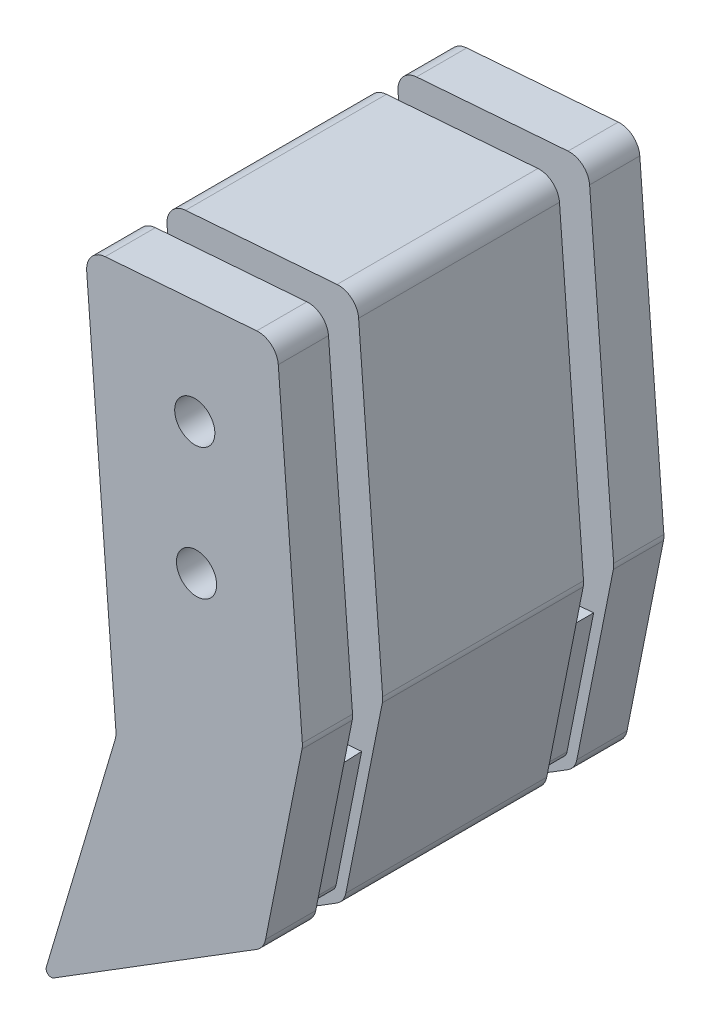
SolidWorks part; units mm, degrees
ref_plane "前视基准面" through (0, 0, 0) normal (0, 0, 1) x (1, 0, 0)
ref_plane "上视基准面" through (0, 0, 0) normal (0, 1, 0) x (1, 0, 0)
ref_plane "右视基准面" through (0, 0, 0) normal (1, 0, 0) x (0, 0, -1)
sketch "草图1" plane through (0, 0, 0) normal (0, 0, 1) x (1, 0, 0)
  line L0 (299.0977, 57.4833) -> (301.7357, 22.832)
  line L1 (315.185, 58.708) -> (317.2959, 30.9803)
  line L2 (317.2959, 30.9803) -> (313.4423, 11.6359)
  line L3 (299.0977, 57.4833) -> (315.185, 58.708)
  line L4 (313.4423, 11.6359) -> (294.7308, 0)
  line L5 (294.7308, 0) -> (301.7357, 22.832)
extrude "凸台-拉伸1" add sketch "草图1" along normal blind 36
ref_plane "基准面1" through (0, 0, 18) normal (0, 0, 1) x (1, 0, 0)
sketch "草图2" plane through (-2.6275, 34.5134, 0) normal (-0.0759, 0.9971, 0) x (0.9971, 0.0759, 0)
  line L4 (318.7321, 0) -> (302.5983, 0)
  line L5 (302.5983, 0) -> (302.5983, -36)
  line L6 (302.5983, -36) -> (318.7321, -36)
  line L7 (318.7321, -36) -> (318.7321, 0)
  line L8 (318.7321, 0) -> (302.5983, 0)
  line L9 (302.5983, 0) -> (302.5983, -36)
  line L10 (302.5983, -36) -> (318.7321, -36)
  line L11 (318.7321, -36) -> (318.7321, 0)
  dimension "D1" = 0
extrude "凸台-拉伸2" add sketch "草图2" along normal blind 6
sketch "草图3" plane through (0, 0, 36) normal (0, 0, 1) x (1, 0, 0)
  line L0 (298.6423, 63.466) -> (301.7357, 22.832) construction
  line L1 (298.6423, 63.466) -> (301.7357, 22.832)
  line L2 (301.7357, 22.832) -> (294.7308, 0) construction
  line L3 (301.7357, 22.832) -> (294.7308, 0)
  line L6 (298.6423, 63.466) -> (295.651, 63.2382)
  line L7 (295.651, 63.2382) -> (298.7444, 22.6043)
  line L9 (294.7308, 0) -> (291.4057, -2.0677)
  line L10 (291.4057, -2.0677) -> (298.7444, 22.6043)
extrude "凸台-拉伸3" add sketch "草图3" against normal up to surface (36 mm away) up to face at (306.7627, 32.2675, 0)
fillet "圆角2" radius 0.5 1 edges at (291.4057, -2.0677, 18)
fillet "圆角4" radius 2 5 edges at (313.4423, 11.6359, 18) (298.7444, 22.6043, 18) (317.2959, 30.9803, 18) (295.651, 63.2382, 18) (314.7295, 64.6907, 18)
ref_plane "基准面2" through (0, 0, 31) normal (0, 0, 1) x (1, 0, 0)
sketch "草图4" plane through (0, 0, 31) normal (0, 0, 1) x (1, 0, 0)
  line L0 (312.8112, 63.5417) -> (297.7211, 62.3929)
  line L1 (296.7999, 61.3199) -> (299.7134, 23.0484)
  line L2 (299.5976, 21.9653) -> (293.1155, 0.1731)
  line L3 (293.1155, 0.1731) -> (312.1782, 12.0274)
  line L4 (312.6309, 12.6813) -> (316.2615, 30.9066)
  line L5 (316.2779, 31.1779) -> (313.8842, 62.6205)
  line L6 (292.5246, -1.3719) -> (312.7063, 11.1782)
  line L7 (313.6116, 12.4859) -> (317.2423, 30.7112)
  line L8 (317.275, 31.2538) -> (314.8814, 62.6964)
  line L9 (312.7353, 64.5389) -> (297.6452, 63.3901)
  line L10 (295.8028, 61.244) -> (298.7163, 22.9725)
  line L11 (298.6391, 22.2504) -> (291.7813, -0.8048)
  line L12 (292.5246, -1.3719) -> (312.7063, 11.1782)
  line L13 (313.6116, 12.4859) -> (317.2423, 30.7112)
  line L14 (317.275, 31.2538) -> (314.8814, 62.6964)
  line L15 (312.7353, 64.5389) -> (297.6452, 63.3901)
  line L16 (295.8028, 61.244) -> (298.7163, 22.9725)
  line L17 (298.6391, 22.2504) -> (291.7813, -0.8048)
  arc A0 (297.7211, 62.3929) -> (296.7999, 61.3199) centre (297.797, 61.3958) ccw
  arc A1 (299.5976, 21.9653) -> (299.7134, 23.0484) centre (296.7221, 22.8206) ccw
  arc A2 (293.1155, 0.1731) -> (293.1155, 0.1731) centre (293.1155, 0.1731) ccw
  arc A3 (312.1782, 12.0274) -> (312.6309, 12.6813) centre (311.6502, 12.8766) ccw
  arc A4 (316.2615, 30.9066) -> (316.2779, 31.1779) centre (315.2808, 31.102) ccw
  arc A5 (313.8842, 62.6205) -> (312.8112, 63.5417) centre (312.8871, 62.5446) ccw
  arc A6 (312.7063, 11.1782) -> (313.6116, 12.4859) centre (311.6502, 12.8766) ccw
  arc A7 (317.2423, 30.7112) -> (317.275, 31.2538) centre (315.2808, 31.102) ccw
  arc A8 (314.8814, 62.6964) -> (312.7353, 64.5389) centre (312.8871, 62.5446) ccw
  arc A9 (297.6452, 63.3901) -> (295.8028, 61.244) centre (297.797, 61.3958) ccw
  arc A10 (298.6391, 22.2504) -> (298.7163, 22.9725) centre (296.7221, 22.8206) ccw
  arc A11 (291.7813, -0.8048) -> (292.5246, -1.3719) centre (292.2606, -0.9473) ccw
  arc A12 (312.7063, 11.1782) -> (313.6116, 12.4859) centre (311.6502, 12.8766) ccw
  arc A13 (317.2423, 30.7112) -> (317.275, 31.2538) centre (315.2808, 31.102) ccw
  arc A14 (314.8814, 62.6964) -> (312.7353, 64.5389) centre (312.8871, 62.5446) ccw
  arc A15 (297.6452, 63.3901) -> (295.8028, 61.244) centre (297.797, 61.3958) ccw
  arc A16 (298.6391, 22.2504) -> (298.7163, 22.9725) centre (296.7221, 22.8206) ccw
  arc A17 (291.7813, -0.8048) -> (292.5246, -1.3719) centre (292.2606, -0.9473) ccw
  dimension "D1" = 0
  dimension "D2" = 1
extrude "切除-拉伸1" cut sketch "草图4" against normal blind 4
mirror "镜向1" about plane through (0, 0, 18) normal (0, 0, 1) of "切除-拉伸1"
sketch "草图5" plane through (316.8153, 24.1187, 0) normal (0.9971, 0.0759, 0) x (0, 0, -1)
  line L0 (-9, 29.0059) -> (-5, 29.0059)
  line L3 (-9, 7.0796) -> (-9, 1.9841)
  line L4 (-5, 7.0796) -> (-5, 38.6132)
  line L5 (-5, 38.6132) -> (-9, 38.6132)
  line L6 (-9, 38.6132) -> (-9, 7.0796)
  line L7 (-9, 7.0796) -> (-5, 7.0796)
  line L8 (-5, 7.0796) -> (-5, 29.0059)
  line L10 (-9, 29.0059) -> (-9, 7.0796)
  line L12 (-31, 38.6132) -> (-31, 7.0796)
  line L13 (-31, 7.0796) -> (-27, 7.0796)
  line L14 (-27, 7.0796) -> (-27, 38.6132)
  line L15 (-27, 38.6132) -> (-31, 38.6132)
  line L16 (-31, 29.0059) -> (-31, 7.0796)
  line L18 (-27, 7.0796) -> (-27, 29.0059)
  line L20 (-9, 1.9841) -> (-5, 1.9841)
  line L21 (-5, 1.9841) -> (-5, 7.0796)
  line L23 (-31, 7.0796) -> (-31, 1.3277)
  line L24 (-27, 7.0796) -> (-27, 1.5448)
  line L25 (-27, 29.0059) -> (-31, 29.0059)
  arc A0 (-27, 1.5448) -> (-31, 1.3277) centre (-9, -367.0247) ccw
  dimension "D1" = 0
  dimension "D2" = 0
extrude "切除-拉伸2" cut sketch "草图5" against normal through all
extrude "切除-拉伸3" cut sketch "草图6" against normal through all and the other way through all
sketch "草图6" plane through (0.5048, 7.5794, 36) normal (0, 0, 1) x (1, -0.0067, 0)
  circle A1 centre (305.1617, 31.8714) radius 2
  circle A3 centre (309.4331, 38.2783) radius 2
sketch "草图7" [suppressed] plane through (0, 0, 27) normal (0, 0, 1) x (1, 0, 0)
  line L6 (295.8028, 61.244) -> (298.7163, 22.9725)
  line L7 (298.6391, 22.2504) -> (291.7813, -0.8048)
  line L8 (292.5246, -1.3719) -> (312.7063, 11.1782)
  line L9 (313.6116, 12.4859) -> (317.2423, 30.7112)
  line L10 (317.275, 31.2538) -> (314.8814, 62.6964)
  line L11 (312.7353, 64.5389) -> (297.6452, 63.3901)
  line L12 (295.8028, 61.244) -> (298.7163, 22.9725)
  line L13 (298.6391, 22.2504) -> (291.7813, -0.8048)
  line L14 (292.5246, -1.3719) -> (312.7063, 11.1782)
  line L15 (313.6116, 12.4859) -> (317.2423, 30.7112)
  line L16 (317.275, 31.2538) -> (314.8814, 62.6964)
  line L17 (312.7353, 64.5389) -> (297.6452, 63.3901)
  circle A0 centre (310.1864, 43.7924) radius 2 construction
  circle A1 centre (310.1864, 43.7924) radius 2
  circle A2 centre (305.8724, 37.4141) radius 2 construction
  circle A3 centre (305.8724, 37.4141) radius 2
  arc A6 (298.6391, 22.2504) -> (298.7163, 22.9725) centre (296.7221, 22.8206) ccw
  arc A7 (291.7813, -0.8048) -> (292.5246, -1.3719) centre (292.2606, -0.9473) ccw
  arc A8 (312.7063, 11.1782) -> (313.6116, 12.4859) centre (311.6502, 12.8766) ccw
  arc A9 (317.2423, 30.7112) -> (317.275, 31.2538) centre (315.2808, 31.102) ccw
  arc A10 (314.8814, 62.6964) -> (312.7353, 64.5389) centre (312.8871, 62.5446) ccw
  arc A11 (297.6452, 63.3901) -> (295.8028, 61.244) centre (297.797, 61.3958) ccw
  arc A12 (298.6391, 22.2504) -> (298.7163, 22.9725) centre (296.7221, 22.8206) ccw
  arc A13 (291.7813, -0.8048) -> (292.5246, -1.3719) centre (292.2606, -0.9473) ccw
  arc A14 (312.7063, 11.1782) -> (313.6116, 12.4859) centre (311.6502, 12.8766) ccw
  arc A15 (317.2423, 30.7112) -> (317.275, 31.2538) centre (315.2808, 31.102) ccw
  arc A16 (314.8814, 62.6964) -> (312.7353, 64.5389) centre (312.8871, 62.5446) ccw
  arc A17 (297.6452, 63.3901) -> (295.8028, 61.244) centre (297.797, 61.3958) ccw
  dimension "D1" = 0
extrude "凸台-拉伸4" [suppressed] add sketch "草图7" along normal blind 1
sketch "草图8" [suppressed] plane through (0, 0, 9) normal (0, 0, -1) x (-1, 0, 0)
  line L6 (-298.7163, 22.9725) -> (-295.8028, 61.244)
  line L7 (-297.6452, 63.3901) -> (-312.7353, 64.5389)
  line L8 (-314.8814, 62.6964) -> (-317.275, 31.2538)
  line L9 (-317.2423, 30.7112) -> (-313.6116, 12.4859)
  line L10 (-312.7063, 11.1782) -> (-292.5246, -1.3719)
  line L11 (-291.7813, -0.8048) -> (-298.6391, 22.2504)
  line L12 (-298.7163, 22.9725) -> (-295.8028, 61.244)
  line L13 (-297.6452, 63.3901) -> (-312.7353, 64.5389)
  line L14 (-314.8814, 62.6964) -> (-317.275, 31.2538)
  line L15 (-317.2423, 30.7112) -> (-313.6116, 12.4859)
  line L16 (-312.7063, 11.1782) -> (-292.5246, -1.3719)
  line L17 (-291.7813, -0.8048) -> (-298.6391, 22.2504)
  circle A0 centre (-305.8724, 37.4141) radius 2 construction
  circle A1 centre (-305.8724, 37.4141) radius 2
  circle A2 centre (-310.1864, 43.7924) radius 2 construction
  circle A3 centre (-310.1864, 43.7924) radius 2
  arc A6 (-298.7163, 22.9725) -> (-298.6391, 22.2504) centre (-296.7221, 22.8206) ccw
  arc A7 (-295.8028, 61.244) -> (-297.6452, 63.3901) centre (-297.797, 61.3958) ccw
  arc A8 (-312.7353, 64.5389) -> (-314.8814, 62.6964) centre (-312.8871, 62.5446) ccw
  arc A9 (-317.275, 31.2538) -> (-317.2423, 30.7112) centre (-315.2808, 31.102) ccw
  arc A10 (-313.6116, 12.4859) -> (-312.7063, 11.1782) centre (-311.6502, 12.8766) ccw
  arc A11 (-292.5246, -1.3719) -> (-291.7813, -0.8048) centre (-292.2606, -0.9473) ccw
  arc A12 (-298.7163, 22.9725) -> (-298.6391, 22.2504) centre (-296.7221, 22.8206) ccw
  arc A13 (-295.8028, 61.244) -> (-297.6452, 63.3901) centre (-297.797, 61.3958) ccw
  arc A14 (-312.7353, 64.5389) -> (-314.8814, 62.6964) centre (-312.8871, 62.5446) ccw
  arc A15 (-317.275, 31.2538) -> (-317.2423, 30.7112) centre (-315.2808, 31.102) ccw
  arc A16 (-313.6116, 12.4859) -> (-312.7063, 11.1782) centre (-311.6502, 12.8766) ccw
  arc A17 (-292.5246, -1.3719) -> (-291.7813, -0.8048) centre (-292.2606, -0.9473) ccw
  dimension "D1" = 0
extrude "凸台-拉伸5" [suppressed] add sketch "草图8" along normal blind 1
sketch "草图9" plane through (316.8153, 24.1187, 0) normal (0.9971, 0.0759, 0) x (0, 0, -1)
  line L0 (-9, 38.6132) -> (-9, 41.4603)
  line L1 (-9, 41.4603) -> (-5, 41.4603)
  line L2 (-5, 41.4603) -> (-5, 38.6132)
  line L3 (-31, 38.6132) -> (-31, 44.4228)
  line L4 (-9, 38.6132) -> (-9, 29.0059)
  line L5 (-9, 29.0059) -> (-5, 29.0059)
  line L6 (-5, 29.0059) -> (-5, 38.6132)
  line L7 (-5, 38.6132) -> (-9, 38.6132)
  line L8 (-9, 38.6132) -> (-9, 29.0059)
  line L9 (-9, 29.0059) -> (-5, 29.0059)
  line L10 (-5, 29.0059) -> (-5, 38.6132)
  line L12 (-31, 44.4228) -> (-27, 44.4228)
  line L13 (-27, 44.4228) -> (-27, 38.6132)
  line L15 (-31, 29.0059) -> (-27, 29.0059)
  line L16 (-27, 29.0059) -> (-27, 38.6132)
  line L17 (-27, 38.6132) -> (-31, 38.6132)
  line L18 (-31, 38.6132) -> (-31, 29.0059)
  line L19 (-31, 29.0059) -> (-27, 29.0059)
  line L20 (-27, 29.0059) -> (-27, 38.6132)
  line L22 (-31, 38.6132) -> (-31, 29.0059)
  dimension "D2" = 0
  dimension "D1" = 0
extrude "切除-拉伸4" cut sketch "草图9" against normal through all
extrude "切除-拉伸5" cut sketch "草图10" against normal through all
sketch "草图10" plane through (66.8668, -81.0923, 36) normal (0, 0, 1) x (0.7884, 0.6152, 0)
  circle A1 centre (264.0005, -51.5968) radius 2
  circle A3 centre (271.8529, -41.2447) radius 2
  point P1 (264.0005, -51.5968)
sketch "草图11" plane through (0, 0, 27) normal (0, 0, 1) x (1, 0, 0)
  line L6 (312.7353, 64.5389) -> (297.6452, 63.3901)
  line L7 (295.8028, 61.244) -> (298.7163, 22.9725)
  line L8 (298.6391, 22.2504) -> (291.7813, -0.8048)
  line L9 (292.5246, -1.3719) -> (312.7063, 11.1782)
  line L10 (313.6116, 12.4859) -> (317.2423, 30.7112)
  line L11 (317.275, 31.2538) -> (314.8814, 62.6964)
  line L12 (312.7353, 64.5389) -> (297.6452, 63.3901)
  line L13 (295.8028, 61.244) -> (298.7163, 22.9725)
  line L14 (298.6391, 22.2504) -> (291.7813, -0.8048)
  line L15 (292.5246, -1.3719) -> (312.7063, 11.1782)
  line L16 (313.6116, 12.4859) -> (317.2423, 30.7112)
  line L17 (317.275, 31.2538) -> (314.8814, 62.6964)
  circle A0 centre (306.7442, 40.6343) radius 2 construction
  circle A1 centre (306.7442, 40.6343) radius 2
  circle A2 centre (306.5667, 53.6263) radius 2 construction
  circle A3 centre (306.5667, 53.6263) radius 2
  arc A6 (314.8814, 62.6964) -> (312.7353, 64.5389) centre (312.8871, 62.5446) ccw
  arc A7 (297.6452, 63.3901) -> (295.8028, 61.244) centre (297.797, 61.3958) ccw
  arc A8 (298.6391, 22.2504) -> (298.7163, 22.9725) centre (296.7221, 22.8206) ccw
  arc A9 (291.7813, -0.8048) -> (292.5246, -1.3719) centre (292.2606, -0.9473) ccw
  arc A10 (312.7063, 11.1782) -> (313.6116, 12.4859) centre (311.6502, 12.8766) ccw
  arc A11 (317.2423, 30.7112) -> (317.275, 31.2538) centre (315.2808, 31.102) ccw
  arc A12 (314.8814, 62.6964) -> (312.7353, 64.5389) centre (312.8871, 62.5446) ccw
  arc A13 (297.6452, 63.3901) -> (295.8028, 61.244) centre (297.797, 61.3958) ccw
  arc A14 (298.6391, 22.2504) -> (298.7163, 22.9725) centre (296.7221, 22.8206) ccw
  arc A15 (291.7813, -0.8048) -> (292.5246, -1.3719) centre (292.2606, -0.9473) ccw
  arc A16 (312.7063, 11.1782) -> (313.6116, 12.4859) centre (311.6502, 12.8766) ccw
  arc A17 (317.2423, 30.7112) -> (317.275, 31.2538) centre (315.2808, 31.102) ccw
  dimension "D1" = 0
extrude "凸台-拉伸6" add sketch "草图11" along normal blind 1
sketch "草图12" plane through (0, 0, 9) normal (0, 0, -1) x (-1, 0, 0)
  line L6 (-298.7163, 22.9725) -> (-295.8028, 61.244)
  line L7 (-297.6452, 63.3901) -> (-312.7353, 64.5389)
  line L8 (-314.8814, 62.6964) -> (-317.275, 31.2538)
  line L9 (-317.2423, 30.7112) -> (-313.6116, 12.4859)
  line L10 (-312.7063, 11.1782) -> (-292.5246, -1.3719)
  line L11 (-291.7813, -0.8048) -> (-298.6391, 22.2504)
  line L12 (-298.7163, 22.9725) -> (-295.8028, 61.244)
  line L13 (-297.6452, 63.3901) -> (-312.7353, 64.5389)
  line L14 (-314.8814, 62.6964) -> (-317.275, 31.2538)
  line L15 (-317.2423, 30.7112) -> (-313.6116, 12.4859)
  line L16 (-312.7063, 11.1782) -> (-292.5246, -1.3719)
  line L17 (-291.7813, -0.8048) -> (-298.6391, 22.2504)
  circle A0 centre (-306.7442, 40.6343) radius 2 construction
  circle A1 centre (-306.7442, 40.6343) radius 2
  circle A2 centre (-306.5667, 53.6263) radius 2 construction
  circle A3 centre (-306.5667, 53.6263) radius 2
  arc A6 (-298.7163, 22.9725) -> (-298.6391, 22.2504) centre (-296.7221, 22.8206) ccw
  arc A7 (-295.8028, 61.244) -> (-297.6452, 63.3901) centre (-297.797, 61.3958) ccw
  arc A8 (-312.7353, 64.5389) -> (-314.8814, 62.6964) centre (-312.8871, 62.5446) ccw
  arc A9 (-317.275, 31.2538) -> (-317.2423, 30.7112) centre (-315.2808, 31.102) ccw
  arc A10 (-313.6116, 12.4859) -> (-312.7063, 11.1782) centre (-311.6502, 12.8766) ccw
  arc A11 (-292.5246, -1.3719) -> (-291.7813, -0.8048) centre (-292.2606, -0.9473) ccw
  arc A12 (-298.7163, 22.9725) -> (-298.6391, 22.2504) centre (-296.7221, 22.8206) ccw
  arc A13 (-295.8028, 61.244) -> (-297.6452, 63.3901) centre (-297.797, 61.3958) ccw
  arc A14 (-312.7353, 64.5389) -> (-314.8814, 62.6964) centre (-312.8871, 62.5446) ccw
  arc A15 (-317.275, 31.2538) -> (-317.2423, 30.7112) centre (-315.2808, 31.102) ccw
  arc A16 (-313.6116, 12.4859) -> (-312.7063, 11.1782) centre (-311.6502, 12.8766) ccw
  arc A17 (-292.5246, -1.3719) -> (-291.7813, -0.8048) centre (-292.2606, -0.9473) ccw
  dimension "D1" = 0
extrude "凸台-拉伸7" add sketch "草图12" along normal blind 1
